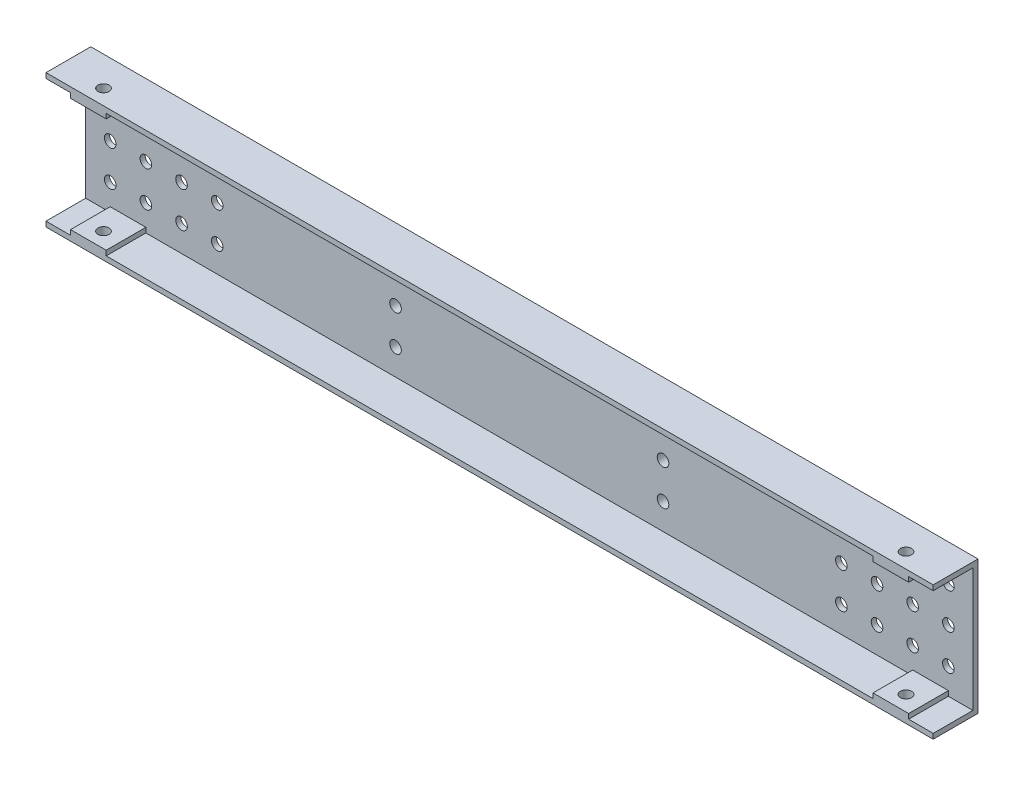
SolidWorks part; units mm, degrees
ref_plane "前视" through (0, 0, 0) normal (0, 0, 1) x (1, 0, 0)
ref_plane "上视" through (0, 0, 0) normal (0, 1, 0) x (1, 0, 0)
ref_plane "右视" through (0, 0, 0) normal (1, 0, 0) x (0, 0, -1)
sketch "草图1" plane through (0, 0, 0) normal (0, 0, 1) x (1, 0, 0)
  line L0 (0, 0) -> (0, 71.3124) construction
  line L1 (0, 71.3124) -> (0, 188.8094) construction
  line L2 (-995, 0) -> (995, 0)
  line L3 (-995, 0) -> (-995, 300)
  line L4 (-995, 300) -> (995, 300)
  line L5 (995, 0) -> (995, 300)
  line L6 (0, 188.8094) -> (0, 294.6471) construction
  line L7 (300, 294.6471) -> (300, -20.2744) construction
  line L8 (49.1838, 70) -> (952.4051, 70) construction
  line L9 (49.1838, 150) -> (1036.2895, 150) construction
  line L10 (49.1838, 230) -> (1036.2895, 230) construction
  circle A0 centre (300, 230) radius 13
  circle A1 centre (300, 150) radius 13
  circle A2 centre (300, 70) radius 13
  circle A3 centre (-300, 70) radius 13
  circle A4 centre (-300, 150) radius 13
  circle A5 centre (-300, 230) radius 13
  dimension "D7" = 26
  dimension "D1" = 1990
  dimension "D2" = 300
  dimension "D3" = 300
  dimension "D4" = 70
  dimension "D5" = 80
  dimension "D6" = 80
extrude "基体-拉伸" add sketch "草图1" along normal blind 11.5
sketch "草图2" plane through (0, 0, 11.5) normal (0, 0, 1) x (1, 0, 0)
  line L0 (995, 0) -> (995, 300) construction
  line L1 (-995, 300) -> (995, 300)
  line L2 (-995, 300) -> (-995, 288.5)
  line L3 (-995, 288.5) -> (-940, 288.5)
  line L4 (995, 300) -> (995, 288.5)
  line L5 (472.8445, 150) -> (989.2832, 150) construction
  line L6 (-995, 0) -> (995, 0)
  line L7 (-995, 0) -> (-995, 11.5)
  line L8 (-995, 11.5) -> (-940, 11.5)
  line L9 (995, 0) -> (995, 11.5)
  line L10 (940, 288.5) -> (940, 277.5)
  line L11 (860, 11.5) -> (860, 22.5)
  line L12 (860, 22.5) -> (940, 22.5)
  line L13 (940, 11.5) -> (940, 22.5)
  line L14 (940, 11.5) -> (995, 11.5)
  line L15 (860, 288.5) -> (860, 277.5)
  line L16 (860, 277.5) -> (940, 277.5)
  line L17 (940, 288.5) -> (995, 288.5)
  line L18 (0, 0) -> (0, 280.097) construction
  line L19 (-940, 11.5) -> (-940, 22.5)
  line L20 (-860, 11.5) -> (-860, 22.5)
  line L21 (-860, 22.5) -> (-940, 22.5)
  line L22 (-940, 288.5) -> (-940, 277.5)
  line L23 (-860, 288.5) -> (-860, 277.5)
  line L24 (-860, 277.5) -> (-940, 277.5)
  line L25 (-860, 288.5) -> (860, 288.5)
  line L26 (-860, 11.5) -> (860, 11.5)
  dimension "D1" = 11.5
  dimension "D3" = 55
  dimension "D4" = 80
  dimension "D5" = 11
  dimension "D6" = 150
extrude "凸台-拉伸1" add sketch "草图2" along normal blind 89
sketch "草图3" plane through (0, 0, 0) normal (0, 0, -1) x (-1, 0, 0)
  line L0 (300, 278.4196) -> (300, 18.6946) construction
  line L1 (0, 0) -> (0, 341.9079) construction
  line L2 (995, 300) -> (995, 0) construction
  line L3 (338.7436, 70) -> (971.2868, 70) construction
  line L4 (995, 0) -> (-995, 0) construction
  line L5 (338.7436, 150) -> (1027.8828, 150) construction
  circle A0 centre (940, 70) radius 13
  circle A1 centre (860, 70) radius 13
  circle A2 centre (780, 70) radius 13
  circle A3 centre (700, 70) radius 13
  circle A4 centre (-940, 70) radius 13
  circle A5 centre (-860, 70) radius 13
  circle A6 centre (-780, 70) radius 13
  circle A7 centre (-700, 70) radius 13
  dimension "D4" = 26
  dimension "D6" = 80
  dimension "D1" = 695
  dimension "D2" = 70
  dimension "D3" = 150
  dimension "D5" = 55
  dimension "D7" = 80
  dimension "D8" = 80
extrude "切除-拉伸1" cut sketch "草图3" against normal through all
pattern_linear "阵列(线性)1" count 3 spacing 80 along (0, 1, 0) of "切除-拉伸1"
sketch "草图7" plane through (0, 0, 0) normal (0, 0, -1) x (-1, 0, 0)
  line L0 (0, 0) -> (0, 358.9057) construction
  line L1 (265, 265) -> (335, 265)
  line L2 (265, 265) -> (265, 35)
  line L3 (265, 35) -> (335, 35)
  line L4 (335, 265) -> (335, 35)
  line L6 (995, 0) -> (-995, 0) construction
  line L7 (300, 333.2202) -> (300, -69.0551) construction
  line L8 (-335, 265) -> (-335, 35)
  line L9 (-265, 35) -> (-335, 35)
  line L10 (-265, 265) -> (-265, 35)
  line L11 (-265, 265) -> (-335, 265)
  circle A0 centre (300, 230) radius 13
  circle A1 centre (300, 150) radius 13
  circle A2 centre (300, 70) radius 13
  circle A3 centre (-300, 70) radius 13
  circle A4 centre (-300, 150) radius 13
  circle A5 centre (-300, 230) radius 13
  dimension "D6" = 26
  dimension "D1" = 265
  dimension "D2" = 70
  dimension "D3" = 230
  dimension "D4" = 35
  dimension "D5" = 35
  dimension "D7" = 70
  dimension "D8" = 80
  dimension "D9" = 80
extrude "凸台-拉伸2" add sketch "草图7" along normal blind 16
sketch "草图8" plane through (0, 300, 0) normal (0, 1, 0) x (-1, 0, 0)
  line L0 (0, 201.8222) -> (0, -191.0723) construction
  line L5 (1045.2587, 66.5) -> (329.7971, 66.5) construction
  line L6 (-995, 100.5) -> (995, 100.5) construction
  line L7 (995, 100.5) -> (995, 0) construction
  circle A0 centre (900, 66.5) radius 12.5
  circle A1 centre (-900, 66.5) radius 12.5
  dimension "D2" = 25
  dimension "D1" = 34
  dimension "D3" = 95
extrude "切除-拉伸2" cut sketch "草图8" against normal through all
